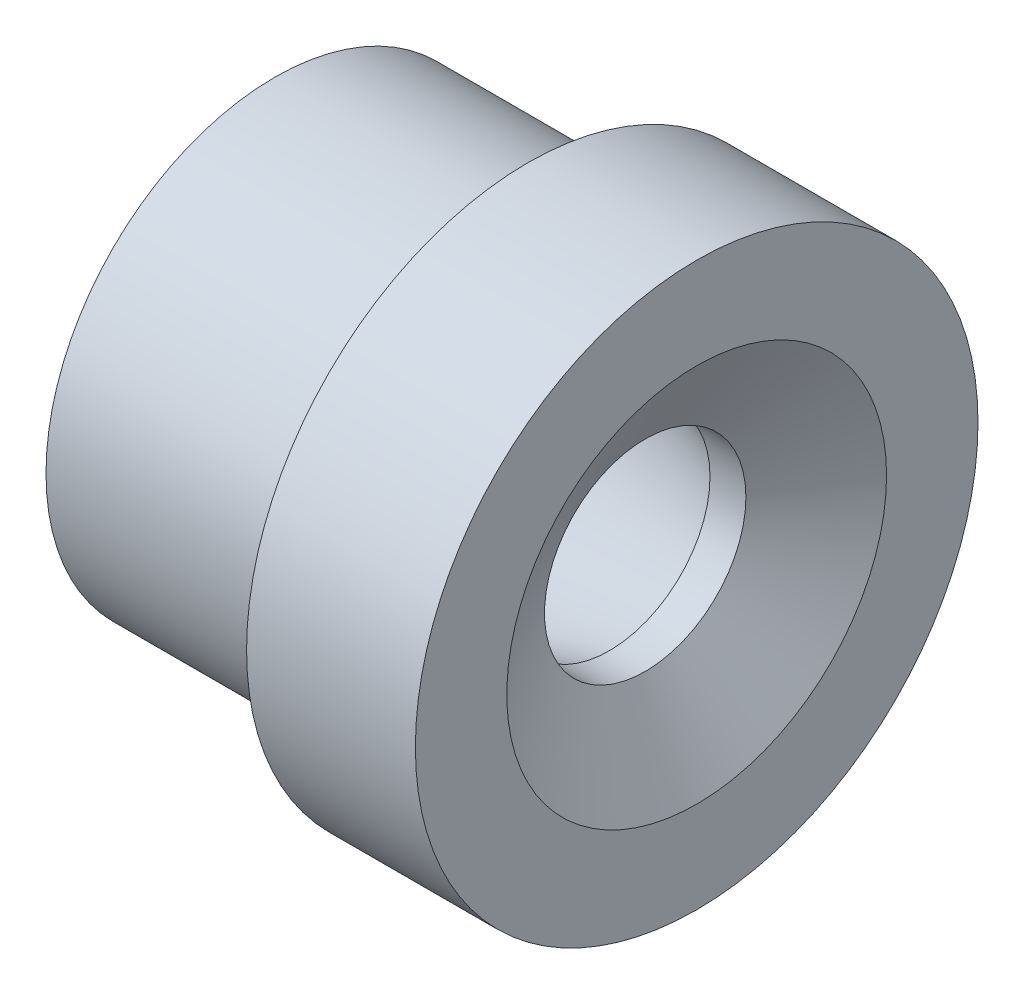
SolidWorks part; units mm, degrees
material "C (Graphite)"
ref_plane "Front Plane" through (0, 0, 0) normal (0, 0, 1) x (1, 0, 0)
ref_plane "Top Plane" through (0, 0, 0) normal (0, 1, 0) x (1, 0, 0)
ref_plane "Right Plane" through (0, 0, 0) normal (1, 0, 0) x (0, 0, -1)
sketch "Sketch1" plane through (0, 0, 0) normal (0, 1, 0) x (1, 0, 0)
  line L0 (0, 0) -> (0, 4.1275)
  line L1 (0, 4.1275) -> (-2.3244, 8.1534)
  line L2 (-2.3244, 8.1534) -> (-3.9449, 8.1534)
  line L3 (-3.9449, 8.1534) -> (-19.05, 4.106)
  line L4 (-19.05, 4.106) -> (-19.05, 2.3749)
  line L5 (-19.05, 2.3749) -> (-7.62, 2.3749)
  line L6 (-7.62, 2.3749) -> (-7.62, 0)
  line L9 (-7.62, 0) -> (0, 0)
  line L10 (5.1187, 12.7) -> (-11.0703, 12.7) construction
  dimension "D1" = 25.4
  dimension "D2" = 9.0932
  dimension "D3" = 60
  dimension "D4" = 15
  dimension "D5" = 17.145
  dimension "D6" = 1.6205
  dimension "D7" = 7.62
  dimension "D8" = 19.05
  dimension "D9" = 20.6502
revolve "Revolve1" add sketch "Sketch1" angle 360 about L10
